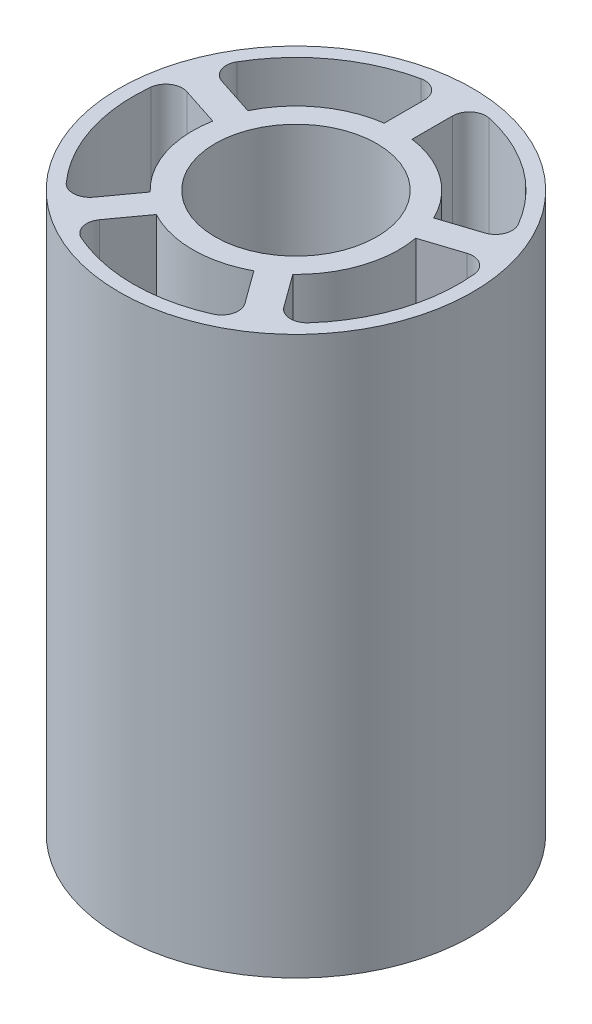
SolidWorks part; units mm, degrees
ref_plane "Front Plane" through (0, 0, 0) normal (0, 0, 1) x (1, 0, 0)
ref_plane "Top Plane" through (0, 0, 0) normal (0, 1, 0) x (1, 0, 0)
ref_plane "Right Plane" through (0, 0, 0) normal (1, 0, 0) x (0, 0, -1)
sketch "Sketch1" plane through (0, 0, 0) normal (0, 1, 0) x (1, 0, 0)
  line L0 (23.5753, 10.2887) -> (16.6606, 8.042)
  line L2 (-2.5, 25.6009) -> (-2.5, 18.3303)
  line L4 (2.5, 25.6009) -> (2.5, 18.3303)
  line L5 (25.1204, 5.5335) -> (18.2057, 3.2867)
  line L6 (17.0704, -19.2421) -> (12.7968, -13.3601)
  line L7 (13.0253, -22.181) -> (8.7517, -16.299)
  line L8 (-13.0253, -22.181) -> (-8.7517, -16.299)
  line L9 (-17.0704, -19.2421) -> (-12.7968, -13.3601)
  line L10 (-25.1204, 5.5335) -> (-18.2057, 3.2867)
  line L11 (-23.5753, 10.2887) -> (-16.6606, 8.042)
  circle A0 centre (0, 0) radius 14.5
  arc A1 (-2.5, 18.3303) -> (-16.6606, 8.042) centre (0, 0) ccw
  circle A2 centre (0, 0) radius 31.685
  arc A3 (-6.1301, 28.5339) -> (-25.2431, 14.6476) centre (0, 0) ccw
  arc A4 (-29.0317, 2.9874) -> (-21.7312, -19.4812) centre (0, 0) ccw
  arc A5 (-18.2057, 3.2867) -> (-12.7968, -13.3601) centre (0, 0) ccw
  arc A6 (16.6606, 8.042) -> (2.5, 18.3303) centre (0, 0) ccw
  arc A7 (25.2431, 14.6476) -> (6.1301, 28.5339) centre (0, 0) ccw
  arc A8 (12.7968, -13.3601) -> (18.2057, 3.2867) centre (0, 0) ccw
  arc A9 (-8.7517, -16.299) -> (8.7517, -16.299) centre (0, 0) ccw
  arc A10 (21.7312, -19.4812) -> (29.0317, 2.9874) centre (0, 0) ccw
  arc A11 (-11.8124, -26.6876) -> (11.8124, -26.6876) centre (0, 0) ccw
  arc A12 (-25.1204, 5.5335) -> (-29.0317, 2.9874) centre (-26.0475, 2.6803) ccw
  arc A13 (-17.0704, -19.2421) -> (-21.7312, -19.4812) centre (-19.4974, -17.4787) cw
  arc A14 (-13.0253, -22.181) -> (-11.8124, -26.6876) centre (-10.5982, -23.9444) ccw
  arc A15 (13.0253, -22.181) -> (11.8124, -26.6876) centre (10.5982, -23.9444) cw
  arc A16 (17.0704, -19.2421) -> (21.7312, -19.4812) centre (19.4974, -17.4787) ccw
  arc A17 (25.1204, 5.5335) -> (29.0317, 2.9874) centre (26.0475, 2.6803) cw
  arc A18 (23.5753, 10.2887) -> (25.2431, 14.6476) centre (22.6483, 13.1419) ccw
  arc A19 (6.1301, 28.5339) -> (2.5, 25.6009) centre (5.5, 25.6009) ccw
  arc A20 (-6.1301, 28.5339) -> (-2.5, 25.6009) centre (-5.5, 25.6009) cw
  arc A21 (-23.5753, 10.2887) -> (-25.2431, 14.6476) centre (-22.6483, 13.1419) cw
  point P5 (0, 0)
  point P26 (0, 0)
  dimension "D1" = 29
  dimension "D2" = 4
  dimension "D3" = 63.37
  dimension "D4" = 2.5
  dimension "D8" = 3
  dimension "D5" = 5
  dimension "D6" = 2.5
  dimension "D7" = 5
extrude "Boss-Extrude1" add sketch "Sketch1" along normal blind 100
